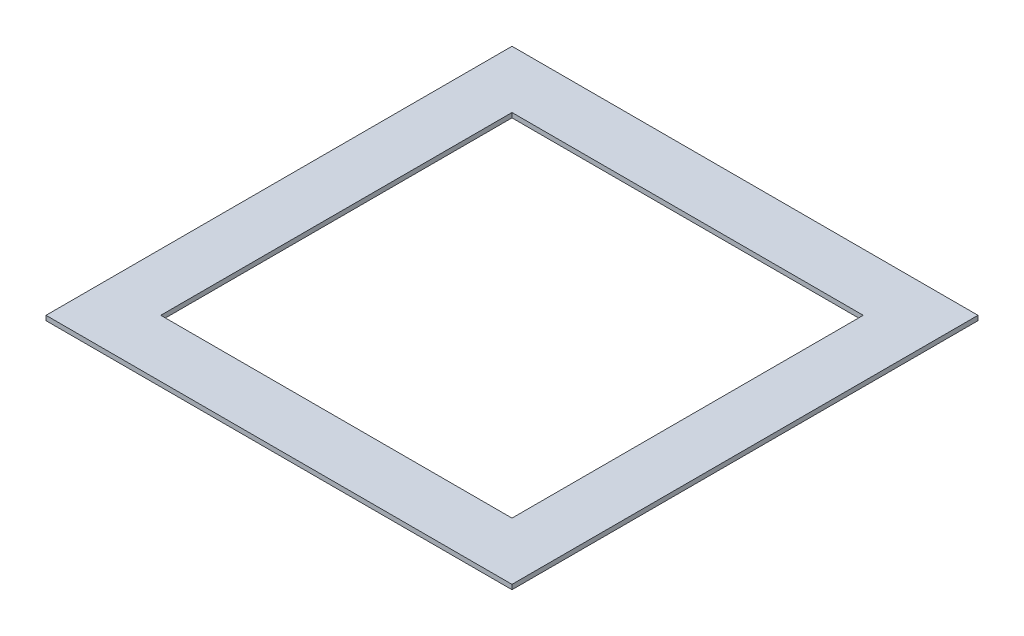
SolidWorks part; units mm, degrees
ref_plane "Alzado" through (0, 0, 0) normal (0, 0, 1) x (1, 0, 0)
ref_plane "Planta" through (0, 0, 0) normal (0, 1, 0) x (1, 0, 0)
ref_plane "Vista lateral" through (0, 0, 0) normal (1, 0, 0) x (0, 0, -1)
sketch "Croquis1" plane through (0, 0, 0) normal (0, 1, 0) x (1, 0, 0)
  line L1 (-49.75, 49.75) -> (49.75, 49.75)
  line L2 (-49.75, 49.75) -> (-49.75, -49.75)
  line L3 (-49.75, -49.75) -> (49.75, -49.75)
  line L4 (49.75, 49.75) -> (49.75, -49.75)
  line L5 (-49.75, 49.75) -> (49.75, -49.75) construction
  line L6 (-49.75, -49.75) -> (49.75, 49.75) construction
  line L7 (-37.5, 37.5) -> (37.5, 37.5)
  line L8 (-37.5, 37.5) -> (-37.5, -37.5)
  line L9 (-37.5, -37.5) -> (37.5, -37.5)
  line L10 (37.5, 37.5) -> (37.5, -37.5)
  line L11 (-37.5, 37.5) -> (37.5, -37.5) construction
  line L12 (-37.5, -37.5) -> (37.5, 37.5) construction
  point P0 (0, 0)
  point P5 (0, 0)
  dimension "D1" = 99.5
  dimension "D2" = 75
extrude "Saliente-Extruir1" add sketch "Croquis1" along normal blind 1
